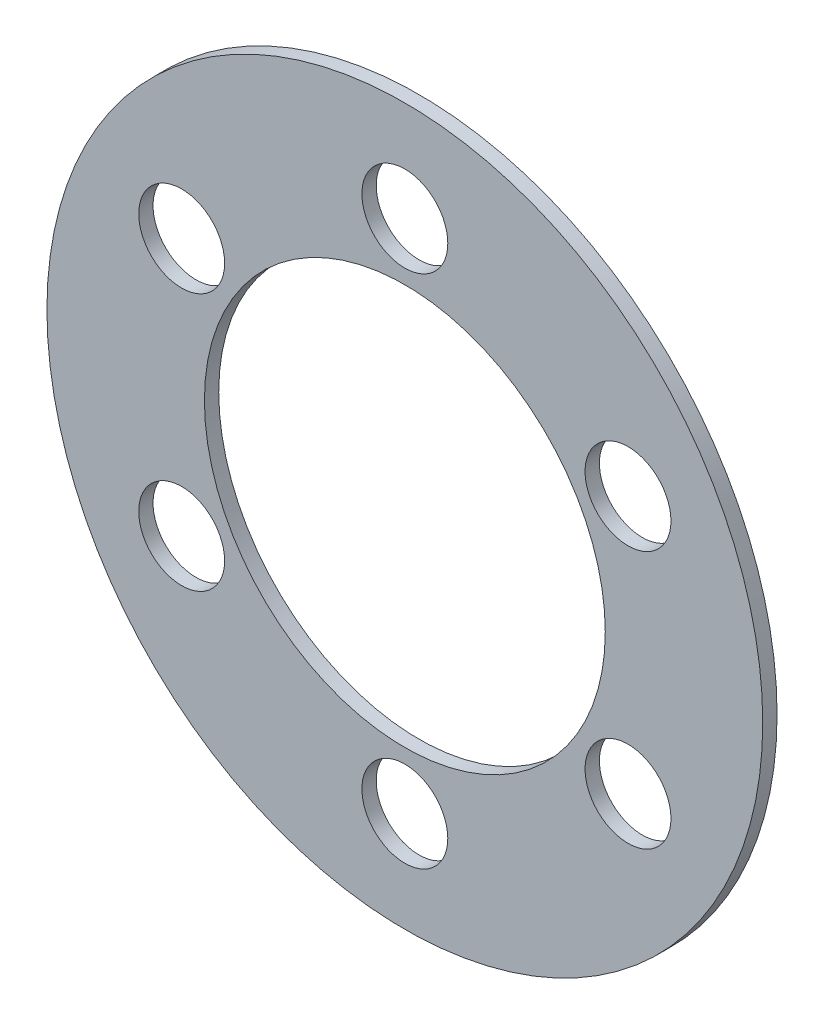
SolidWorks part; units mm, degrees
material "Бутил"
ref_plane "Спереди" through (0, 0, 0) normal (0, 0, 1) x (1, 0, 0)
ref_plane "Сверху" through (0, 0, 0) normal (0, 1, 0) x (1, 0, 0)
ref_plane "Справа" through (0, 0, 0) normal (1, 0, 0) x (0, 0, -1)
sketch "Эскиз1" plane through (0, 0, 0) normal (0, 0, 1) x (1, 0, 0)
  line L0 (0, 0) -> (0, 9) construction
  circle A0 centre (0, 0) radius 7
  circle A1 centre (0, 0) radius 12.5
  circle A2 centre (0, 9) radius 1.5
  circle A3 centre (7.7942, 4.5) radius 1.5
  circle A4 centre (7.7942, -4.5) radius 1.5
  circle A5 centre (0, -9) radius 1.5
  circle A6 centre (-7.7942, -4.5) radius 1.5
  circle A7 centre (-7.7942, 4.5) radius 1.5
  point P7 (0, 0)
  dimension "D1" = 14
  dimension "D2" = 25
  dimension "D3" = 3
  dimension "D4" = 9
  dimension "D6" = 9
  dimension "D5" = 6
extrude "Бобышка-Вытянуть1" add sketch "Эскиз1" along normal blind 0.5
